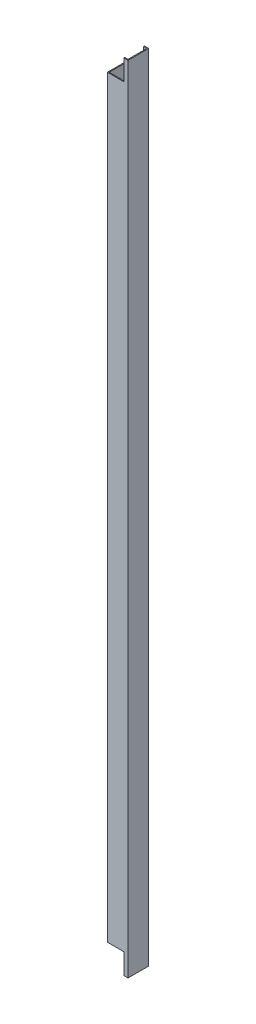
SolidWorks part; units mm, degrees
ref_plane "Front Plane" through (0, 0, 0) normal (0, 0, 1) x (1, 0, 0)
ref_plane "Top Plane" through (0, 0, 0) normal (0, 1, 0) x (1, 0, 0)
ref_plane "Right Plane" through (0, 0, 0) normal (1, 0, 0) x (0, 0, -1)
sketch "Sketch1" plane through (0, 0, 0) normal (0, 1, 0) x (1, 0, 0)
  line L0 (0, 0) -> (0, 50)
  line L1 (0, 50) -> (50, 50)
  line L2 (50, 50) -> (50, 0)
  line L3 (50, 0) -> (0, 0)
  line L4 (2.2, 47.8) -> (47.8, 47.8)
  line L5 (47.8, 47.8) -> (47.8, 2.2)
  line L6 (47.8, 2.2) -> (2.2, 2.2)
  line L7 (2.2, 2.2) -> (2.2, 47.8)
  dimension "D1" = 50
  dimension "D2" = 50
  dimension "D3" = 2.2
extrude "Boss-Extrude1" add sketch "Sketch1" along normal blind 1923
sketch "Sketch2" plane through (0, 0, 0) normal (0, 0, 1) x (1, 0, 0)
  line L0 (0, 0) -> (0, 50)
  line L1 (0, 1923) -> (0, 0) construction
  line L2 (0, 50) -> (40, 50)
  line L3 (40, 50) -> (40, 0)
  line L5 (40, 0) -> (0, 0)
  line L6 (0, 1923) -> (40, 1923)
  line L7 (0, 1923) -> (50, 1923) construction
  line L8 (40, 1923) -> (40, 1873)
  line L9 (40, 1873) -> (0, 1873)
  line L10 (0, 1873) -> (0, 1923)
  dimension "D1" = 50
  dimension "D2" = 40
  dimension "D3" = 50
  dimension "D4" = 40
extrude "Cut-Extrude2" cut sketch "Sketch2" against normal blind 50
equation "\"SquareTube_length\"=1923.0"
equation "\"D1@Boss-Extrude1\"=\"SquareTube_length\""
equation "\"SquareTube_inBack1_cutDepth50_R\"=50"
equation "\"D1@Sketch2\" = \"SquareTube_inBack2_cutDepth50_R\""
equation "\"SquareTube_inBack1_cutDepth50_L\"=50"
equation "\"D3@Sketch2\" = \"SquareTube_inBack2_cutDepth50_L\""
equation "\"CarBeamWidth\"=700.0"
equation "\"MetalSheet_3mm_length\"=5030.0"
equation "\"MetalSheet_3mm_width\"=1923.0"
equation "\"MetalSheet_3mm_FloorCut_L_length\"=1764.0"
equation "\"MetalSheet_3mm_FloorCut_L_disdance\"=1665.0"
equation "\"MetalSheet_3mm_FloorCut_R_length\"=1764.0"
equation "\"MetalSheet_3mm_FloorCut_R_disdance\"=1665.0"
equation "\"indoorHeight\"=1940.0"
equation "\"x\"=66.0"
equation "\"da\"=62.0"
equation "\"SquareTube_wheel_length\"= 750"
equation "\"channelSteel_length\"=5030.0"
equation "\"SquareTube_inFront1_cutDepth50_R\"=0.5"
equation "\"SquareTube_inFront1_cutDepth50_L\"=0.5"
equation "\"SquareTube_inFront2_cutDepth50_R\"=0.5"
equation "\"SquareTube_inFront2_cutDepth50_L\"=0.5"
equation "\"SquareTube_inFront3_cutDepth50_R\"=0.5"
equation "\"SquareTube_inFront3_cutDepth50_L\"=0.5"
equation "\"SquareTube_inFront4_cutDepth50_R\"=0.5"
equation "\"SquareTube_inFront4_cutDepth50_L\"=0.5"
equation "\"SquareTube_inFront5_cutDepth50_R\"=50"
equation "\"SquareTube_inFront5_cutDepth50_L\"=50"
equation "\"SquareTube_inFront6_cutDepth50_R\"=50"
equation "\"SquareTube_inFront6_cutDepth50_L\"=50"
equation "\"SquareTube_inFront7_cutDepth50_R\"=50"
equation "\"SquareTube_inFront7_cutDepth50_L\"=50"
equation "\"SquareTube_inFront8_cutDepth50_R\"=50"
equation "\"SquareTube_inFront8_cutDepth50_L\"=50"
equation "\"SquareTube_inFront9_cutDepth50_R\"=50"
equation "\"SquareTube_inFront9_cutDepth50_L\"=50"
equation "\"SquareTube_inFront10_cutDepth50_R\"=50"
equation "\"SquareTube_inFront10_cutDepth50_L\"=50"
equation "\"SquareTube_inBack2_cutDepth50_R\"=50"
equation "\"SquareTube_inBack2_cutDepth50_L\"=50"
equation "\"SquareTube_inBack3_cutDepth50_R\"=50"
equation "\"SquareTube_inBack3_cutDepth50_L\"=50"
equation "\"SquareTube_inBack4_cutDepth50_R\"=50"
equation "\"SquareTube_inBack4_cutDepth50_L\"=50"
equation "\"SquareTube_inBack5_cutDepth50_R\"=50"
equation "\"SquareTube_inBack5_cutDepth50_L\"=50"
equation "\"SquareTube_inBack6_cutDepth50_R\"=0.5"
equation "\"SquareTube_inBack6_cutDepth50_L\"=0.5"
equation "\"SquareTube_inFront11_cutDepth50_R\"=50"
equation "\"SquareTube_inFront11_cutDepth50_L\"=50"
equation "\"SquareTube_inFront12_cutDepth50_R\"=50"
equation "\"SquareTube_inFront12_cutDepth50_L\"=50"
equation "\"SquareTube_inFront13_cutDepth50_R\"=50"
equation "\"SquareTube_inFront13_cutDepth50_L\"=50"
equation "\"SquareTube_inFront14_cutDepth50_R\"=50"
equation "\"SquareTube_inFront14_cutDepth50_L\"=50"
equation "\"SquareTube_inBack7_cutDepth50_R\"=0.5"
equation "\"SquareTube_inBack7_cutDepth50_L\"=0.5"
equation "\"SquareTube_inBack8_cutDepth50_R\"=0.5"
equation "\"SquareTube_inBack8_cutDepth50_L\"=0.5"
